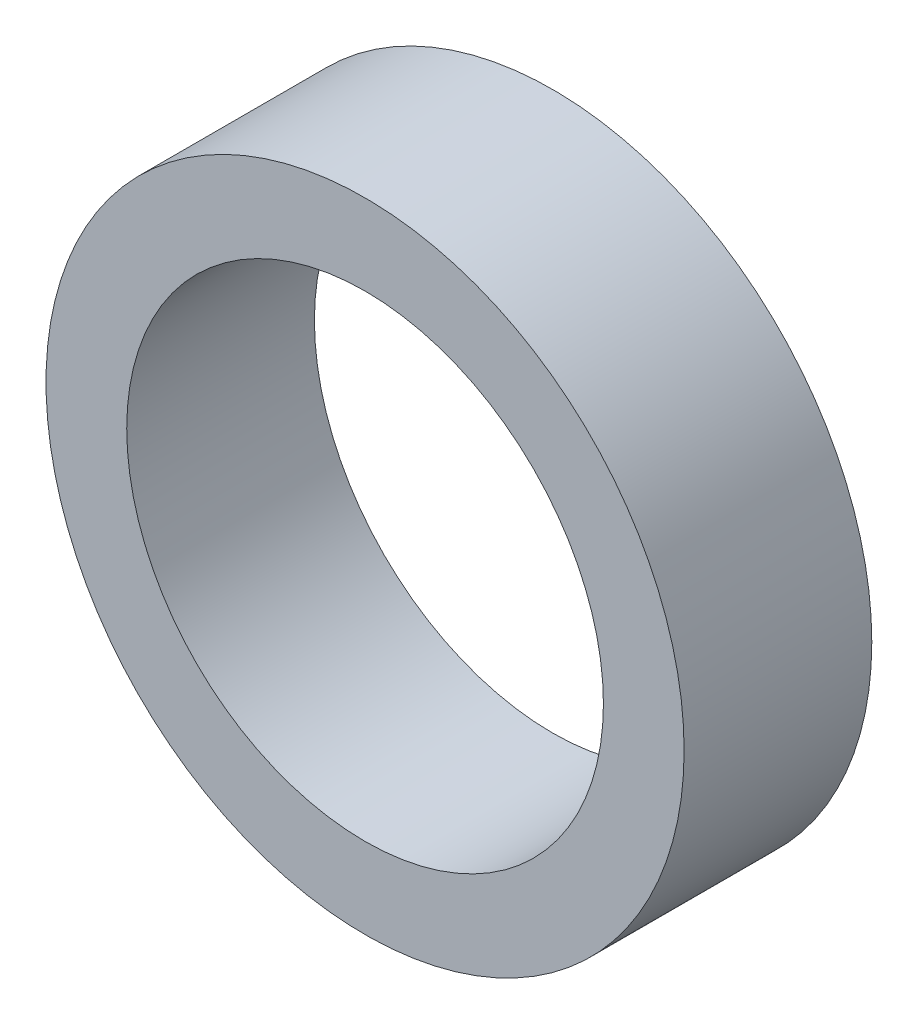
SolidWorks part; units mm, degrees
ref_plane "Plano frontal" through (0, 0, 0) normal (0, 0, 1) x (1, 0, 0)
ref_plane "Plano superior" through (0, 0, 0) normal (0, 1, 0) x (1, 0, 0)
ref_plane "Plano direito" through (0, 0, 0) normal (1, 0, 0) x (0, 0, -1)
sketch "Esboço1" plane through (0, 0, 0) normal (1, 0, 0) x (0, 0, -1)
  line L0 (0, 0) -> (34, 0) construction
  line L8 (0, 12.7) -> (10, 12.7)
  line L9 (0, 12.7) -> (0, 17)
  line L10 (0, 17) -> (10, 17)
  line L11 (10, 12.7) -> (10, 17)
  dimension "D1" = 25.4
  dimension "D2" = 34
  dimension "D3" = 10
revolve "Revolução1" add sketch "Esboço1" angle 360 about L0
